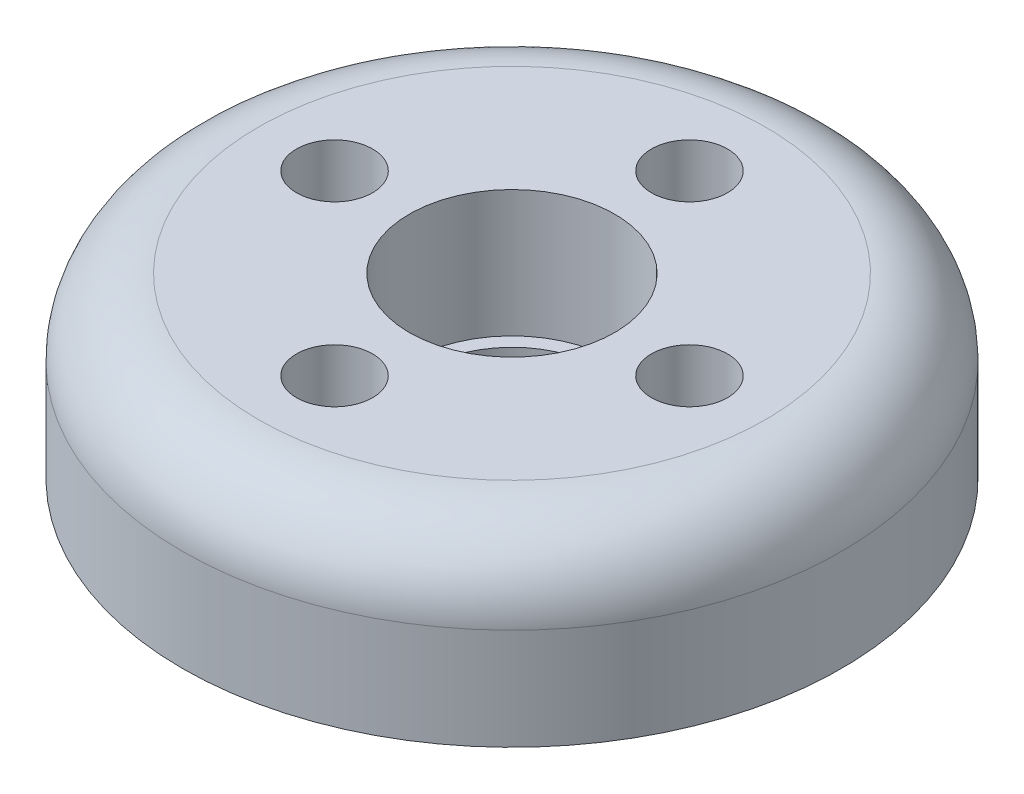
SolidWorks part; units mm, degrees
ref_plane "Front Plane" through (0, 0, 0) normal (0, 0, 1) x (1, 0, 0)
ref_plane "Top Plane" through (0, 0, 0) normal (0, 1, 0) x (1, 0, 0)
ref_plane "Right Plane" through (0, 0, 0) normal (1, 0, 0) x (0, 0, -1)
sketch "Sketch1" plane through (0, 0, 0) normal (0, 1, 0) x (1, 0, 0)
  circle A0 centre (0, 0) radius 13
  circle A1 centre (0, 0) radius 3.5
  circle A3 centre (0, 7) radius 1.5
  circle A4 centre (7, 0) radius 1.5
  circle A5 centre (0, -7) radius 1.5
  circle A6 centre (-7, 0) radius 1.5
extrude "Boss-Extrude1" add sketch "Sketch1" along normal blind 7
sketch "Sketch2" plane through (0, 7, 0) normal (0, 1, 0) x (1, 0, 0)
  circle A0 centre (0, 0) radius 4.05
extrude "Cut-Extrude1" cut sketch "Sketch2" against normal blind 5
fillet "Fillet1" radius 3 1 edges at (0, 7, 13)
